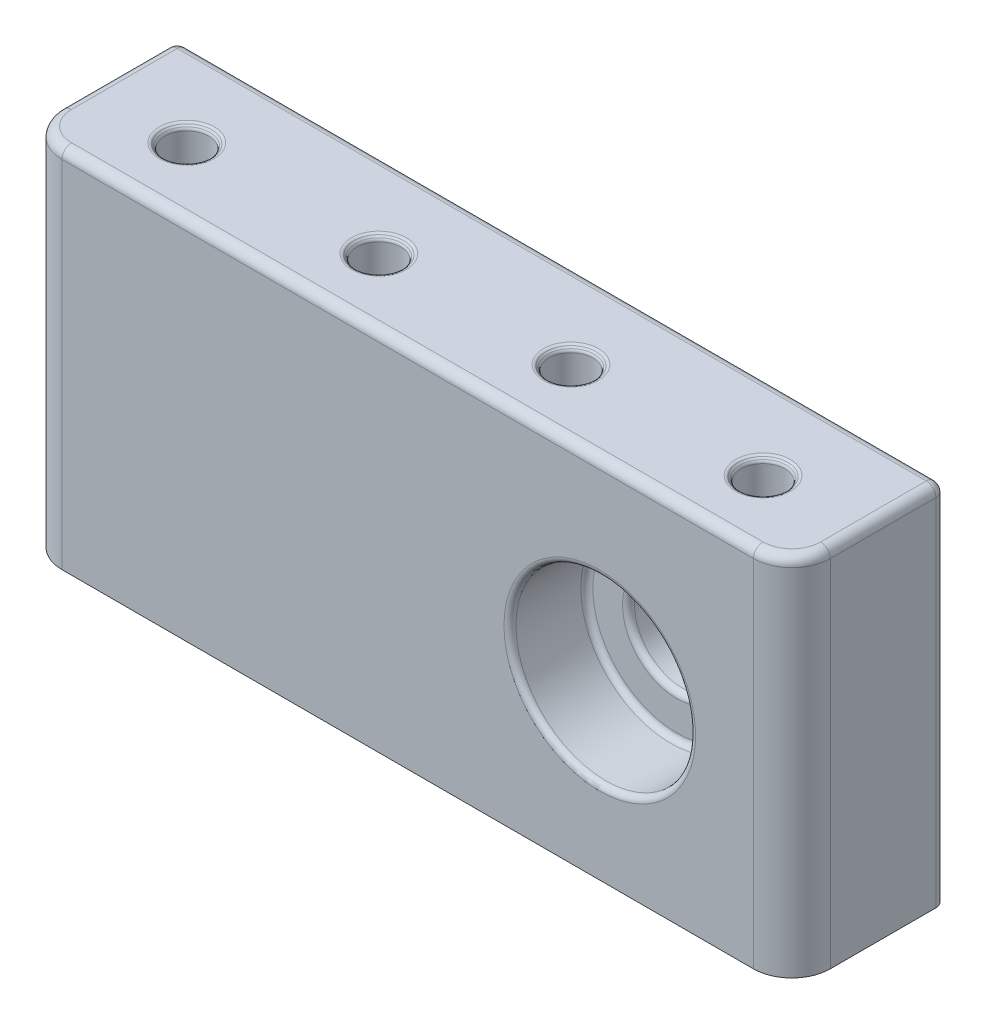
SolidWorks part; units mm, degrees
ref_plane "Front Plane" through (0, 0, 0) normal (0, 0, 1) x (1, 0, 0)
ref_plane "Top Plane" through (0, 0, 0) normal (0, 1, 0) x (1, 0, 0)
ref_plane "Right Plane" through (0, 0, 0) normal (1, 0, 0) x (0, 0, -1)
sketch "Sketch2" plane through (0, 0, 0) normal (0, 0, 1) x (1, 0, 0)
  line L1 (-20, -9.5) -> (20, -9.5)
  line L2 (-20, -9.5) -> (-20, 9.5)
  line L3 (-20, 9.5) -> (20, 9.5)
  line L4 (20, -9.5) -> (20, 9.5)
  line L5 (-20, -9.5) -> (20, 9.5) construction
  line L6 (-20, 9.5) -> (20, -9.5) construction
  point P0 (0, 0)
  dimension "D1" = 40
  dimension "D2" = 19
extrude "Boss-Extrude1" add sketch "Sketch2" along normal blind 8
fillet "Fillet1" radius 2 2 edges at (20, 0, 8) (-20, 0, 8)
sketch "Sketch5" plane through (0, 9.5, 0) normal (0, 1, 0) x (1, 0, 0)
  line L0 (18, -8) -> (-18, -8) construction
  line L1 (-20, -6) -> (-20, 0) construction
  circle A0 centre (-15, -4.5) radius 1.15
  circle A1 centre (-5, -4.5) radius 1.15
  circle A2 centre (5, -4.5) radius 1.15
  circle A3 centre (15, -4.5) radius 1.15
  dimension "D1" = 2.3
  dimension "D2" = 3.5
  dimension "D3" = 5
  dimension "D5" = 10
  dimension "D4" = 4
extrude "Cut-Extrude3" cut sketch "Sketch5" against normal blind 7
chamfer "Chamfer1" distance 0.2 angle 45 8 edges at (15, 9.5, 5.65) (15, 2.5, 5.65) (5, 9.5, 5.65) (5, 2.5, 5.65) (-5, 9.5, 5.65) (-5, 2.5, 5.65) (-15, 9.5, 5.65) (-15, 2.5, 5.65)
fillet "Fillet5" radius 0.2 8 edges at (15, 9.5, 3.15) (15, 9.3, 3.35) (-15, 9.5, 3.15) (-15, 9.3, 3.35) (-5, 9.5, 3.15) (-5, 9.3, 3.35) (5, 9.5, 3.15) (5, 9.3, 3.35)
fillet "Fillet2" radius 0.5 8 edges at (20, 9.5, 3) (19.4142, 9.5, 7.4142) (-20, 9.5, 3) (-19.4142, 9.5, 7.4142) (0, 9.5, 8) (0, 9.5, 0) (20, 0, 0) (-20, 0, 0)
sketch "Sketch3" plane through (0, 0, 8) normal (0, 0, 1) x (1, 0, 0)
  line L0 (-18, -9.5) -> (18, -9.5) construction
  line L2 (20, 9) -> (20, -9.5) construction
  circle A0 centre (10, -0.5) radius 4.675
  dimension "D1" = 9.35
  dimension "D2" = 9
  dimension "D3" = 10
extrude "Cut-Extrude1" cut sketch "Sketch3" against normal blind 4
sketch "Sketch4" plane through (0, 0, 4) normal (0, 0, 1) x (1, 0, 0)
  circle A0 centre (10, -0.5) radius 2.5
  circle A1 centre (10, -0.5) radius 4.675 construction
  dimension "D1" = 5
extrude "Cut-Extrude2" cut sketch "Sketch4" against normal blind 4
chamfer "Chamfer3" distance 1.5 angle 45 1 edges at (12.5, -0.5, 0)
fillet "Fillet4" radius 0.3125 5 edges at (14.675, -0.5, 4) (14.675, -0.5, 8) (12.5, -0.5, 4) (6, -0.5, 0) (7.5, -0.5, 1.5)
